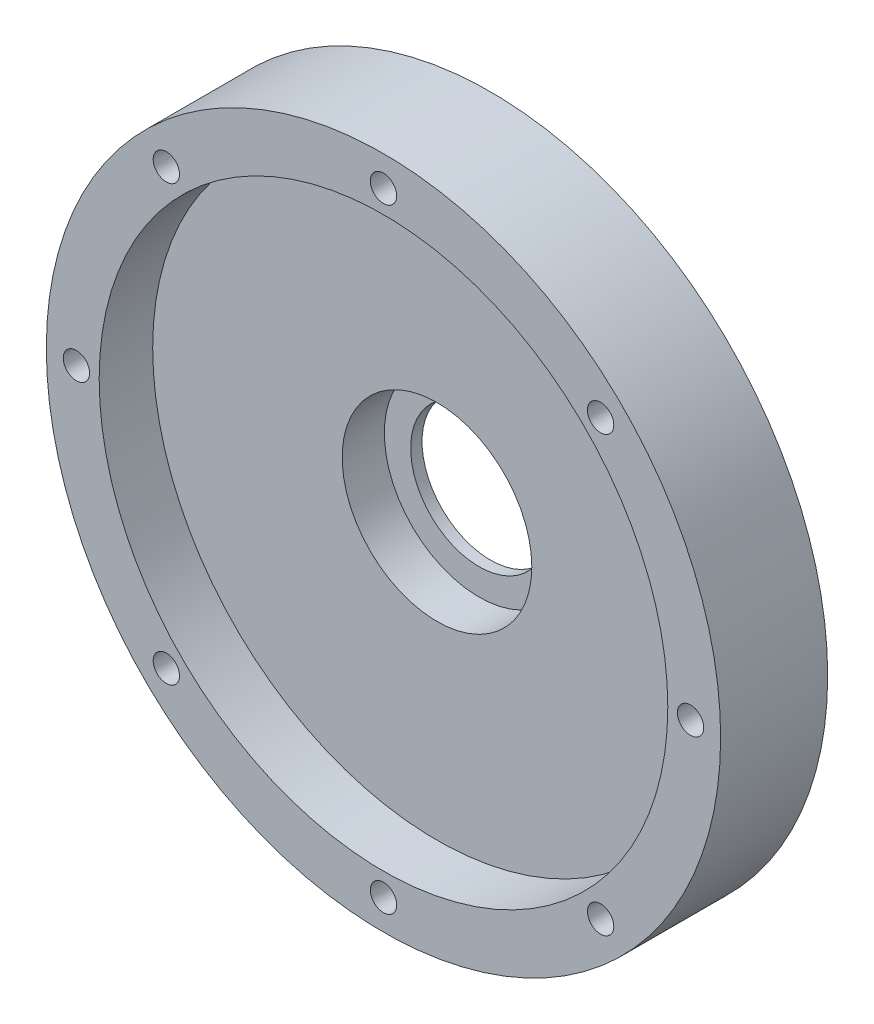
SolidWorks part; units mm, degrees
material "ABS"
ref_plane "Front Plane" through (0, 0, 0) normal (0, 0, 1) x (1, 0, 0)
ref_plane "Top Plane" through (0, 0, 0) normal (0, 1, 0) x (1, 0, 0)
ref_plane "Right Plane" through (0, 0, 0) normal (1, 0, 0) x (0, 0, -1)
sketch "Sketch1" plane through (0, 0, 0) normal (0, 0, 1) x (1, 0, 0)
  circle A0 centre (0, 0) radius 32.004
  dimension "D1" = 64.008
extrude "Boss-Extrude1" add sketch "Sketch1" along normal blind 10.16
sketch "Sketch2" plane through (0, 0, 10.16) normal (0, 0, 1) x (1, 0, 0)
  circle A0 centre (0, 0) radius 26.9875
  dimension "D1" = 53.975
extrude "Cut-Extrude1" cut sketch "Sketch2" against normal blind 5.08
sketch "Sketch3" plane through (0, 0, 5.08) normal (0, 0, 1) x (1, 0, 0)
  circle A0 centre (0, 0) radius 9
  dimension "D1" = 18
extrude "Cut-Extrude2" cut sketch "Sketch3" against normal blind 4
sketch "Sketch4" plane through (0, 0, 1.08) normal (0, 0, 1) x (1, 0, 0)
  circle A0 centre (0, 0) radius 6.5
  dimension "D1" = 13
extrude "Cut-Extrude3" cut sketch "Sketch4" against normal through all
sketch "Sketch5" plane through (0, 0, 10.16) normal (0, 0, 1) x (1, 0, 0)
  line L0 (0, 0) -> (0, 32.004) construction
  line L2 (0, 0) -> (22.6302, 22.6302) construction
  line L3 (0, 0) -> (32.004, 0) construction
  line L4 (0, 0) -> (22.6302, -22.6302) construction
  line L5 (0, 0) -> (0, -32.004) construction
  line L6 (0, 0) -> (-22.6302, -22.6302) construction
  line L7 (0, 0) -> (-32.004, 0) construction
  line L8 (0, 0) -> (-22.6302, 22.6302) construction
  line L9 (0, 0) -> (0, 29.1465) construction
  circle A0 centre (0, 0) radius 32.004 construction
  point P6 (0, 29.1465)
  point P15 (20.6097, 20.6097)
  point P17 (29.1465, 0)
  point P19 (20.6097, -20.6097)
  point P21 (0, -29.1465)
  point P23 (-20.6097, -20.6097)
  point P25 (-29.1465, 0)
  point P27 (-20.6097, 20.6097)
  dimension "D1" = 29.1465
  dimension "D2" = 8
hole_wizard "M3x0.5 Tapped Hole1" positions "Sketch5" profile "Sketch6" tap size "M3x0.5" standard "ANSI Metric" end condition through all
sketch "Sketch6" plane through (-20.6097, 20.6097, 10.16) normal (1, 0, 0) x (0, -1, 0)
  line L0 (0, 0) -> (0, 10.16)
  line L1 (0, 10.16) -> (1.25, 10.16)
  line L2 (1.25, 10.16) -> (1.25, 0)
  line L5 (1.25, 0) -> (0, 0)
  line L11 (0, -6.35) -> (0, 107.95) construction
  dimension "Thru Tap Drill Dia." = 2.5
  dimension "Thru Tap Drill Depth" = 10.16
cosmetic thread "Hole Thread1" parameters "D2"=3
cosmetic thread "Hole Thread2" parameters "D2"=3
cosmetic thread "Hole Thread3" parameters "D2"=3
cosmetic thread "Hole Thread4" parameters "D2"=3
cosmetic thread "Hole Thread5" parameters "D2"=3
cosmetic thread "Hole Thread6" parameters "D2"=3
cosmetic thread "Hole Thread7" parameters "D2"=3
cosmetic thread "Hole Thread8" parameters "D2"=3
